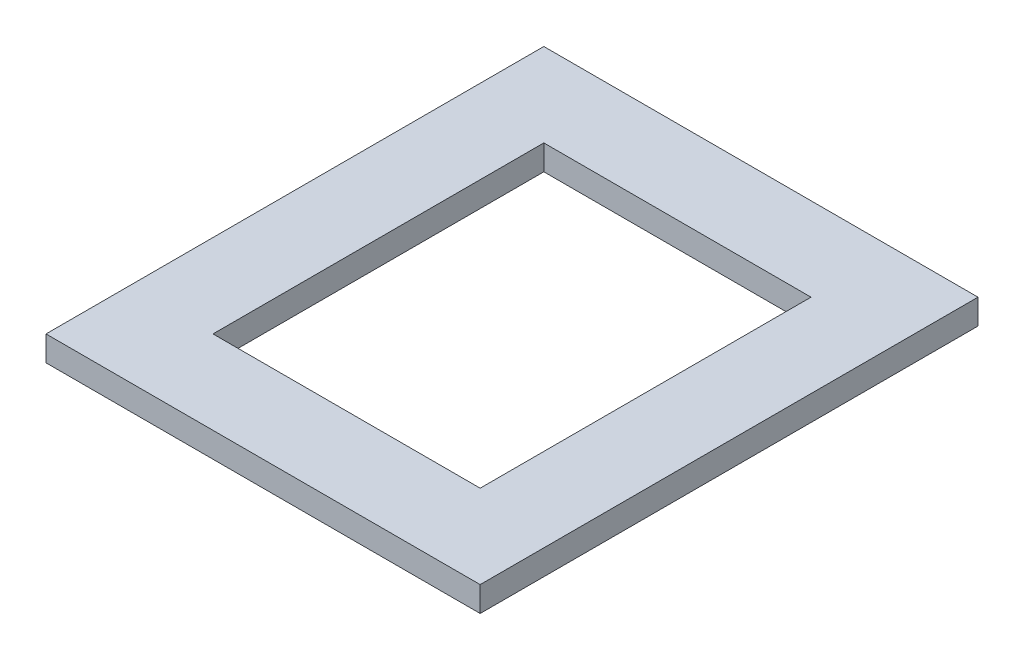
SolidWorks part; units mm, degrees
ref_plane "Front Plane" through (0, 0, 0) normal (0, 0, 1) x (1, 0, 0)
ref_plane "Top Plane" through (0, 0, 0) normal (0, 1, 0) x (1, 0, 0)
ref_plane "Right Plane" through (0, 0, 0) normal (1, 0, 0) x (0, 0, -1)
sketch "Sketch1" plane through (0, 0, 0) normal (0, 1, 0) x (1, 0, 0)
  line L1 (-16, -19.813) -> (16, -19.813)
  line L2 (-16, -19.813) -> (-16, 19.813)
  line L3 (-16, 19.813) -> (16, 19.813)
  line L4 (16, -19.813) -> (16, 19.813)
  line L5 (-16, -19.813) -> (16, 19.813) construction
  line L6 (-16, 19.813) -> (16, -19.813) construction
  line L7 (-26, -29.813) -> (26, -29.813)
  line L8 (-26, -29.813) -> (-26, 29.813)
  line L9 (-26, 29.813) -> (26, 29.813)
  line L10 (26, -29.813) -> (26, 29.813)
  line L11 (-26, -29.813) -> (26, 29.813) construction
  line L12 (-26, 29.813) -> (26, -29.813) construction
  point P0 (0, 0)
  point P5 (0, 0)
  point P11 (0, 0)
  dimension "D1" = 10
  dimension "D2" = 10
  dimension "D3" = 32
extrude "Boss-Extrude1" add sketch "Sketch1" along normal blind 3
